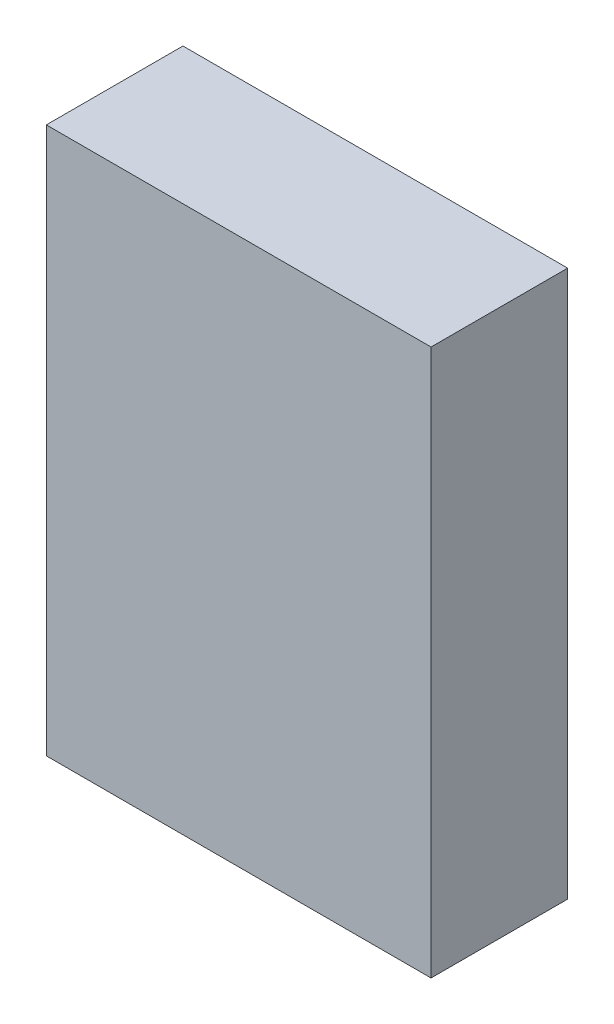
SolidWorks part; units mm, degrees
ref_plane "Front Plane" through (0, 0, 0) normal (0, 0, 1) x (1, 0, 0)
ref_plane "Top Plane" through (0, 0, 0) normal (0, 1, 0) x (1, 0, 0)
ref_plane "Right Plane" through (0, 0, 0) normal (1, 0, 0) x (0, 0, -1)
sketch "Sketch1" plane through (0, 0, 0) normal (0, 0, 1) x (1, 0, 0)
  line L1 (0, 0) -> (-140.8, 0)
  line L2 (0, 0) -> (0, -200)
  line L3 (0, -200) -> (-140.8, -200)
  line L4 (-140.8, 0) -> (-140.8, -200)
  dimension "D1" = 140.8
  dimension "D2" = 200
extrude "Boss-Extrude1" add sketch "Sketch1" along normal blind 50
